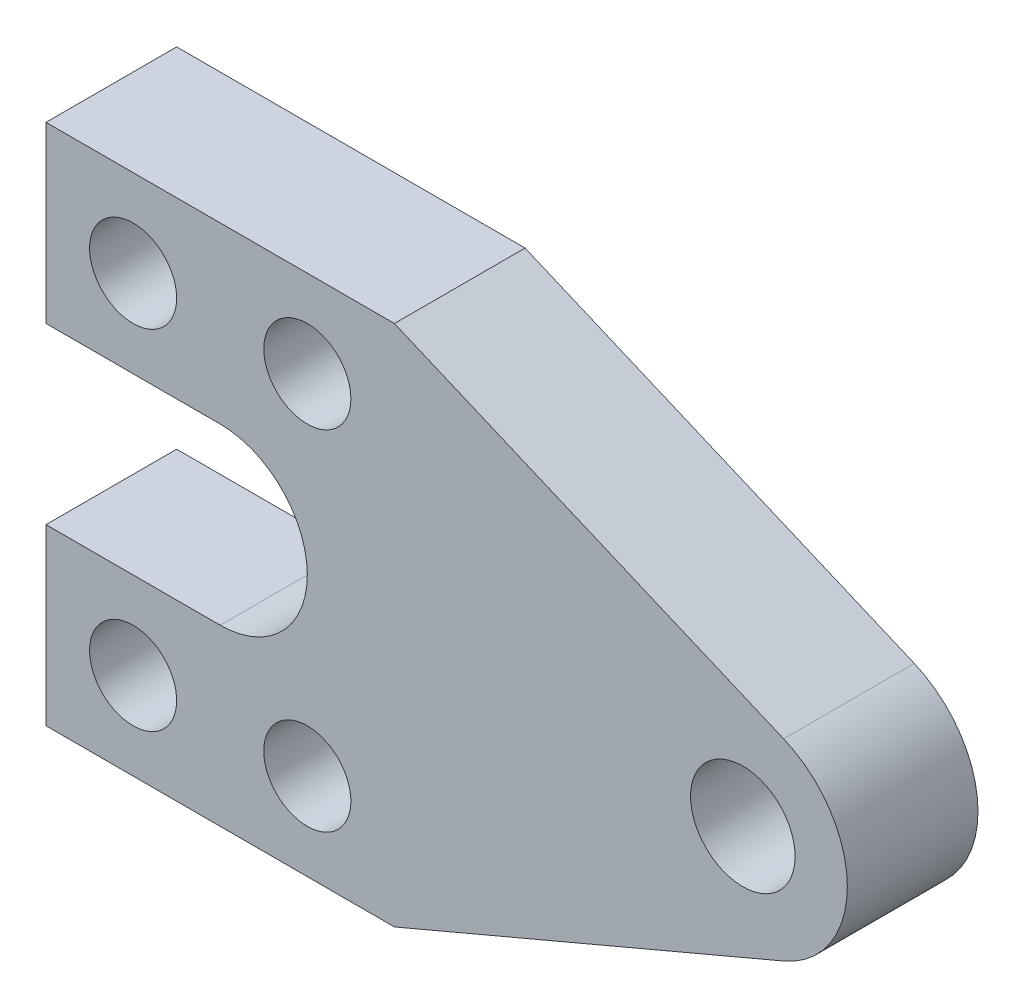
SolidWorks part; units mm, degrees
ref_plane "Front Plane" through (0, 0, 0) normal (0, 0, 1) x (1, 0, 0)
ref_plane "Top Plane" through (0, 0, 0) normal (0, 1, 0) x (1, 0, 0)
ref_plane "Right Plane" through (0, 0, 0) normal (1, 0, 0) x (0, 0, -1)
sketch "Sketch1" plane through (0, 0, 0) normal (0, 0, 1) x (1, 0, 0)
  line L0 (0, 0) -> (-15101.6242, 0) construction
  line L1 (0, 0) -> (0, 15101.6242) construction
  line L2 (-80, 30) -> (-40, 30)
  line L3 (-80, -30) -> (-40, -30)
  line L4 (-40, 30) -> (4.6856, 11.0474)
  line L5 (-40, -30) -> (4.6856, -11.0474)
  line L6 (-80, 30) -> (-80, 10)
  line L7 (-80, 10) -> (-60, 10)
  line L8 (-60, -10) -> (-80, -10)
  line L9 (-80, -10) -> (-80, -30)
  circle A0 centre (0, 0) radius 6
  arc A1 (4.6856, -11.0474) -> (4.6856, 11.0474) centre (0, 0) ccw
  arc A2 (-60, 10) -> (-60, -10) centre (-60, 0) cw
  circle A3 centre (-70, 20) radius 5
  circle A4 centre (-50, 20) radius 5
  circle A5 centre (-70, -20) radius 5
  circle A6 centre (-50, -20) radius 5
  point P22 (0, 0)
  point P25 (-79.7508, 29.7059)
  dimension "D1" = 40
  dimension "D2" = 12
  dimension "D3" = 24
  dimension "D6" = 20
  dimension "D8" = 10
  dimension "D9" = 20
  dimension "D4" = 80
  dimension "D5" = 30
  dimension "D7" = 20
  dimension "D10" = 10
  dimension "D11" = 10
extrude "Boss-Extrude1" add sketch "Sketch1" along normal blind 15
